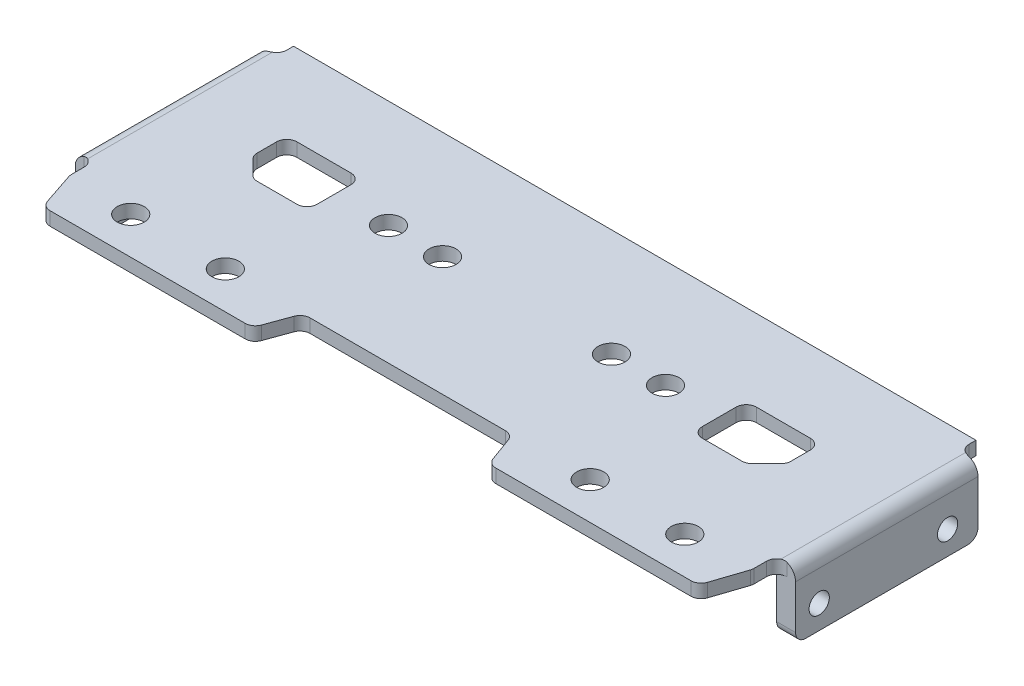
SolidWorks part; units mm, degrees
material "1060 Alloy"
ref_plane "Front Plane" through (0, 0, 0) normal (0, 0, 1) x (1, 0, 0)
ref_plane "Top Plane" through (0, 0, 0) normal (0, 1, 0) x (1, 0, 0)
ref_plane "Right Plane" through (0, 0, 0) normal (1, 0, 0) x (0, 0, -1)
sketch "Sketch1" plane through (0, 0, 0) normal (0, 1, 0) x (1, 0, 0)
  line L0 (0, 6) -> (2, 0)
  line L1 (2, 0) -> (33, 0)
  line L2 (0, 6) -> (0, 39.095)
  line L3 (0, 39.095) -> (101, 39.095)
  line L4 (101, 6) -> (101, 39.095)
  line L5 (33, 0) -> (35, 5.5)
  line L6 (50.5, 90.357) -> (50.5, -12.167) construction
  line L7 (35, 5.5) -> (66, 5.5)
  line L9 (68, 0) -> (66, 5.5)
  line L10 (99, 0) -> (68, 0)
  line L11 (101, 6) -> (99, 0)
  line L12 (11, 22.095) -> (14, 19.095)
  line L13 (11, 27.095) -> (22, 27.095)
  line L14 (11, 27.095) -> (11, 22.095)
  line L15 (14, 19.095) -> (22, 19.095)
  line L16 (22, 27.095) -> (22, 19.095)
  line L17 (90, 27.095) -> (90, 22.095)
  line L18 (90, 22.095) -> (87, 19.095)
  line L19 (87, 19.095) -> (79, 19.095)
  line L20 (79, 27.095) -> (79, 19.095)
  line L21 (90, 27.095) -> (79, 27.095)
  circle A0 centre (9.5, 5.5) radius 2
  circle A1 centre (23.5, 5.5) radius 2
  circle A2 centre (77.5, 5.5) radius 2
  circle A3 centre (91.5, 5.5) radius 2
  circle A4 centre (30, 23.1498) radius 2
  circle A5 centre (38, 23.1498) radius 2
  circle A6 centre (63, 23.1498) radius 2
  circle A7 centre (71, 23.1498) radius 2
  point P12 (50.5, 39.095)
  point P14 (50.5, 5.5)
  dimension "D1" = 4
  dimension "D2" = 9.5
  dimension "D8" = 5.5
  dimension "D9" = 14
  dimension "D16" = 4
  dimension "D17" = 8
  dimension "D18" = 8
  dimension "D3" = 6
  dimension "D4" = 2
  dimension "D5" = 31
  dimension "D6" = 5.5
  dimension "D7" = 2
  dimension "D10" = 11
  dimension "D11" = 8
  dimension "D12" = 12
  dimension "D14" = 5
  dimension "D15" = 8
extrude "Boss-Extrude1" add sketch "Sketch1" along normal blind 2
sketch "Sketch2" plane through (0, 2, 0) normal (0, 1, 0) x (1, 0, 0)
  line L0 (0, 39.095) -> (0, 6) construction
  line L1 (0, 36.595) -> (-2.8, 36.595)
  line L2 (0, 36.595) -> (0, 9.595)
  line L3 (0, 9.595) -> (-2.8, 9.595)
  line L4 (-2.8, 36.595) -> (-2.8, 9.595)
  line L5 (101, 39.095) -> (0, 39.095) construction
  line L6 (50.5, 66.5583) -> (50.5, 11.6317) construction
  line L7 (101, 9.595) -> (103.8, 9.595)
  line L8 (103.8, 36.595) -> (103.8, 9.595)
  line L9 (101, 36.595) -> (103.8, 36.595)
  line L10 (101, 36.595) -> (101, 9.595)
  point P11 (50.5, 39.095)
  dimension "D1" = 2.8
  dimension "D2" = 2.5
  dimension "D3" = 27
extrude "Boss-Extrude2" add sketch "Sketch2" against normal blind 10
sketch "Sketch3" plane through (103.8, 0, 0) normal (1, 0, 0) x (0, 0, -1)
  line L0 (9.595, -8) -> (9.595, 2) construction
  line L1 (36.595, -8) -> (36.595, 2) construction
  line L2 (9.595, -8) -> (36.595, -8) construction
  circle A0 centre (13.095, -4.5) radius 1.5
  circle A1 centre (32.095, -4.5) radius 1.5
  dimension "D1" = 3
  dimension "D2" = 3.5
  dimension "D3" = 4.5
  dimension "D4" = 3.5
extrude "Cut-Extrude1" cut sketch "Sketch3" against normal through all
fillet "Fillet1" radius 1.5 26 edges at (-1.4, -8, -9.595) (-1.4, -8, -36.595) (0, 1, -9.595) (0, 1, -6) (2, 1, 0) (0, 1, -36.595) (102.4, -8, -36.595) (101, 1, -36.595) (102.4, -8, -9.595) (101, 1, -9.595) (101, 1, -6) (99, 1, 0) (66, 1, -5.5) (68, 1, 0) (90, 1, -27.095) (79, 1, -27.095) (90, 1, -22.095) (87, 1, -19.095) (79, 1, -19.095) (35, 1, -5.5) (33, 1, 0) (11, 1, -27.095) (11, 1, -22.095) (14, 1, -19.095) (22, 1, -19.095) (22, 1, -27.095)
fillet "Fillet2" radius 2 2 edges at (-2.8, 2, -23.095) (103.8, 2, -23.095)
